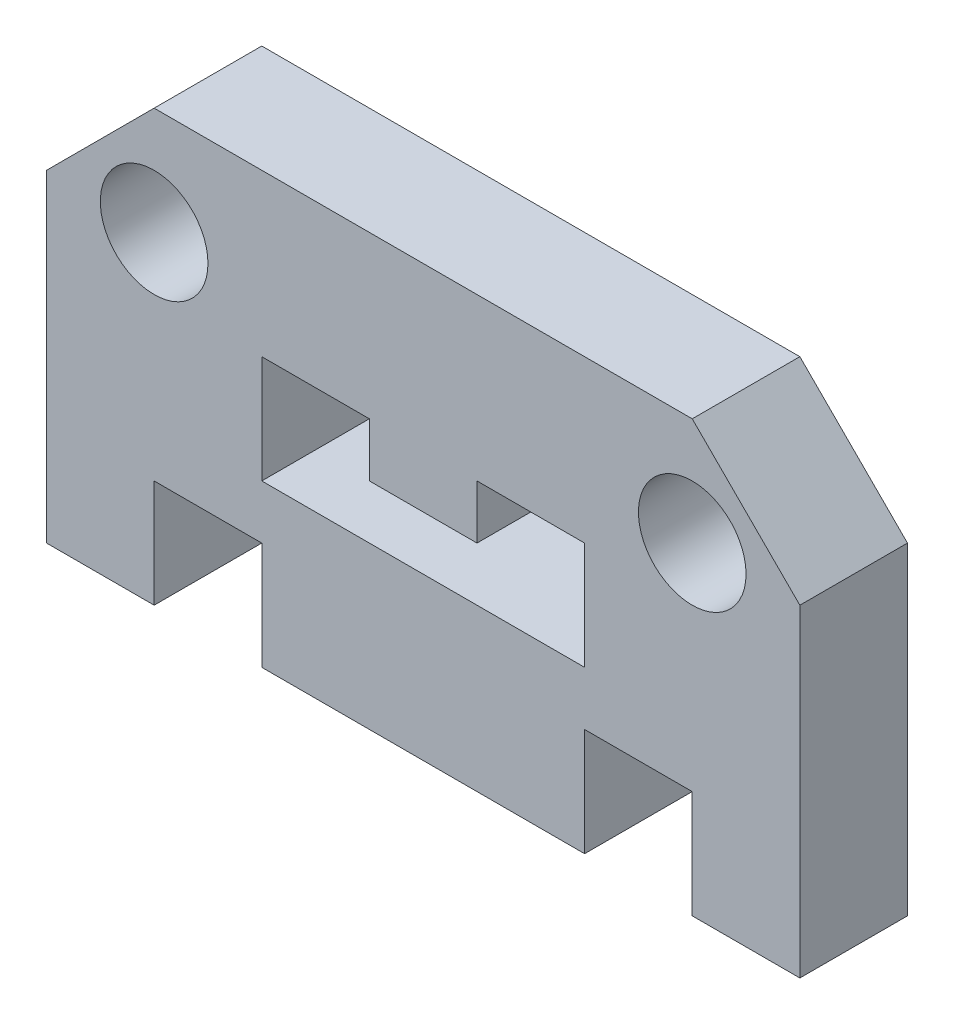
SolidWorks part; units mm, degrees
ref_plane "Front Plane" through (0, 0, 0) normal (0, 0, 1) x (1, 0, 0)
ref_plane "Top Plane" through (0, 0, 0) normal (0, 1, 0) x (1, 0, 0)
ref_plane "Right Plane" through (0, 0, 0) normal (1, 0, 0) x (0, 0, -1)
sketch "Sketch1" plane through (0, 0, 0) normal (0, 0, 1) x (1, 0, 0)
  line L0 (-1050, 0) -> (-25, 0) construction
  line L1 (0, 0) -> (0, 50000) construction
  line L2 (-35, 30) -> (-25, 40)
  line L3 (-25, 40) -> (25, 40)
  line L4 (-35, 30) -> (-35, 0)
  line L5 (-35, 0) -> (-25, 0)
  line L6 (35, 30) -> (35, 0)
  line L7 (25, 40) -> (35, 30)
  line L8 (-25, 0) -> (-25, 10)
  line L9 (-25, 10) -> (-15, 10)
  line L10 (-15, 10) -> (-15, 0)
  line L11 (15, 15) -> (-15, 15)
  line L12 (-15, 25) -> (-5, 25)
  line L13 (-5, 25) -> (-5, 20)
  line L14 (-5, 20) -> (5, 20)
  line L15 (-15, 25) -> (-15, 15)
  line L16 (15, 25) -> (15, 15)
  line L17 (5, 25) -> (5, 20)
  line L18 (15, 25) -> (5, 25)
  line L19 (15, 10) -> (15, 0)
  line L20 (25, 10) -> (15, 10)
  line L21 (25, 0) -> (25, 10)
  line L22 (-15, 0) -> (15, 0) construction
  line L23 (-15, 0) -> (15, 0)
  line L24 (25, 0) -> (50000, 0) construction
  line L25 (25, 0) -> (35, 0)
  circle A0 centre (-25, 30) radius 5
  circle A1 centre (25, 30) radius 5
  point P5 (-35, 40)
  point P8 (35, 40)
  point P30 (0, 20)
  point P31 (0, 15)
  dimension "D7" = 10
  dimension "D1" = 40
  dimension "D2" = 70
  dimension "D3" = 10
  dimension "D4" = 45
  dimension "D5" = 10
  dimension "D6" = 45
  dimension "D8" = 10
  dimension "D9" = 10
  dimension "D10" = 10
  dimension "D11" = 5
  dimension "D12" = 10
  dimension "D13" = 15
  dimension "D14" = 10
  dimension "D15" = 5
extrude "Boss-Extrude1" add sketch "Sketch1" along normal blind 10
